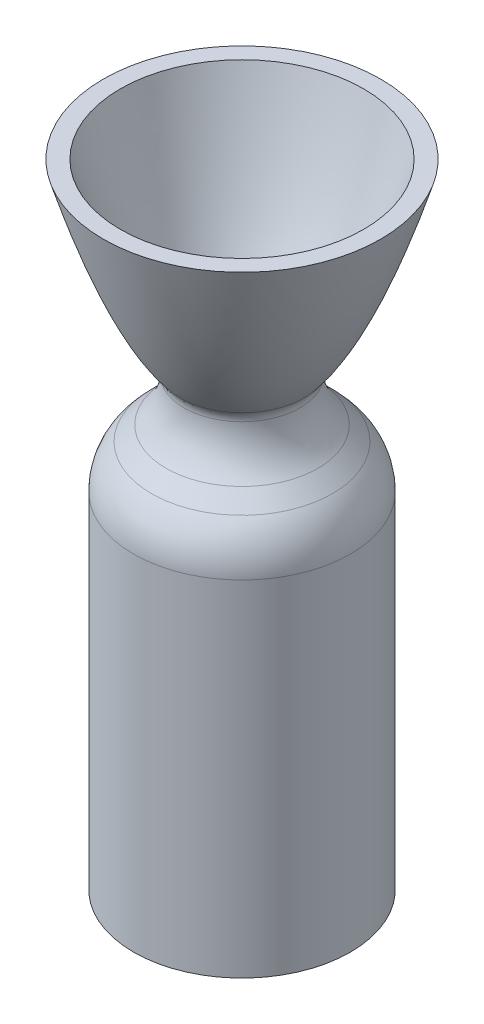
SolidWorks part; units mm, degrees
material "AISI 1020"
ref_plane "Front Plane" through (0, 0, 0) normal (0, 0, 1) x (1, 0, 0)
ref_plane "Top Plane" through (0, 0, 0) normal (0, 1, 0) x (1, 0, 0)
ref_plane "Right Plane" through (0, 0, 0) normal (1, 0, 0) x (0, 0, -1)
sketch "Sketch1" plane through (0, 0, 0) normal (0, 0, 1) x (1, 0, 0)
  line L0 (-0.0055, 165.816) -> (-0.0055, -134.6871) construction
  line L1 (71.7275, 109.9275) -> (81.7275, 109.9275)
  line L4 (53.8815, -59.7275) -> (53.8815, -262.9275)
  line L7 (63.8815, -59.761) -> (63.8815, -262.9447)
  line L8 (53.8815, -262.9275) -> (63.8815, -262.9447)
  spline S0 degree 2 poles (26.7953, 6.5094) (49.2614, 34.6361) (71.7275, 109.9275) knots 0 0 0 1 1 1 construction
  spline S1 degree 2 poles (26.7953, 6.5094) (49.2614, 34.6361) (71.7275, 109.9275) knots 0 0 0 1 1 1
  spline S2 degree 4 poles (24.1269, -0.7179) (24.126, -0.7018) (24.1243, -0.6738) (24.121, -0.6546) (24.115, -0.5166) (24.1058, -0.4369) (24.0994, -0.1066) (24.0979, 0.0018) (24.102, 0.2678) (24.1085, 0.4272) (24.1205, 0.6469) (24.1414, 0.9016) (24.1752, 1.2027) (24.2265, 1.5422) (24.2905, 1.8812) (24.3671, 2.2165) (24.4563, 2.5494) (24.5577, 2.8783) (24.6716, 3.2035) (24.7972, 3.5238) (24.9353, 3.8398) (25.0841, 4.1494) (25.246, 4.4549) (25.4165, 4.7515) (25.6025, 5.0459) (25.7918, 5.3257) (26.0044, 5.6109) (26.1789, 5.8331) (26.3663, 6.0501) (26.5046, 6.2088) (26.757, 6.4728) (26.837, 6.5526) (27.1016, 6.806) (27.1881, 6.8783) (27.2854, 6.9667) (27.3038, 6.9803) (27.3264, 7.0004) knots 0 0 0 0 0 0.005192 0.010384 0.020768 0.041536 0.082569 0.102427 0.122284 0.142142 0.162 0.201716 0.241431 0.281147 0.320863 0.360578 0.400294 0.44001 0.479725 0.519441 0.559156 0.598872 0.638588 0.678303 0.718019 0.757735 0.79745 0.837166 0.857024 0.876882 0.916597 0.958047 0.979024 0.989512 1 1 1 1 1 construction
  spline S3 degree 4 poles (24.0991, 0.0002) (24.0991, 0.0361) (24.0996, 0.1103) (24.102, 0.2678) (24.1085, 0.4272) (24.1205, 0.6469) (24.1414, 0.9016) (24.1752, 1.2027) (24.2265, 1.5422) (24.2905, 1.8812) (24.3671, 2.2165) (24.4563, 2.5494) (24.5577, 2.8783) (24.6716, 3.2035) (24.7972, 3.5238) (24.9353, 3.8398) (25.0841, 4.1494) (25.246, 4.4549) (25.4165, 4.7515) (25.6025, 5.0459) (25.7918, 5.3257) (26.0044, 5.6109) (26.1789, 5.8331) (26.3663, 6.0501) (26.5046, 6.2088) (26.6704, 6.3823) (26.7445, 6.4586) (26.7953, 6.5094) knots 0.082569 0.082569 0.082569 0.082569 0.082569 0.102427 0.122284 0.142142 0.162 0.201716 0.241431 0.281147 0.320863 0.360578 0.400294 0.44001 0.479725 0.519441 0.559156 0.598872 0.638588 0.678303 0.718019 0.757735 0.79745 0.837166 0.857024 0.876882 0.916597 0.916597 0.916597 0.916597 0.916597
  spline S4 degree 4 poles (24.2082, 2.808) (24.2014, 2.7166) (24.1882, 2.5518) (24.1642, 2.1754) (24.1352, 1.6881) (24.1148, 1.1018) (24.103, 0.6556) (24.0988, 0.1104) (24.0988, -0.0999) (24.102, -0.543) (24.1083, -0.824) (24.1178, -1.1947) (24.1304, -1.5133) (24.1462, -1.8618) (24.1652, -2.1935) (24.1928, -2.6179) (24.2323, -3.1219) (24.3033, -3.8798) (24.4231, -4.8863) (24.5995, -6.0566) (24.8509, -7.385) (25.1518, -8.7034) (25.5018, -10.0095) (25.9004, -11.3017) (26.3469, -12.5779) (26.841, -13.8367) (27.3817, -15.076) (27.9685, -16.2944) (28.6001, -17.4898) (29.2765, -18.6611) (29.9954, -19.8056) (30.758, -20.9237) (31.4592, -21.8743) (32.0887, -22.6733) (32.6241, -23.3203) (33.0723, -23.8398) (33.5085, -24.3297) (33.9358, -24.7883) (34.2456, -25.1137) (34.6121, -25.4859) (34.7661, -25.6398) (35.1509, -26.0187) (35.4776, -26.3286) (35.905, -26.7273) (36.2395, -27.0242) (36.5192, -27.2707) (36.6465, -27.3798) (36.7148, -27.4387) (36.7496, -27.4686) knots 0 0 0 0 0 0.010393 0.020785 0.041571 0.062104 0.072371 0.082638 0.092575 0.102512 0.112449 0.122387 0.132324 0.142261 0.152198 0.162135 0.18201 0.201884 0.241633 0.281382 0.32113 0.360879 0.400628 0.440377 0.480126 0.519874 0.559623 0.599372 0.639121 0.67887 0.718618 0.758367 0.798116 0.81799 0.837865 0.857739 0.877613 0.897488 0.907425 0.917362 0.927629 0.937896 0.958429 0.979215 0.989607 0.994804 1 1 1 1 1 construction
  spline S5 degree 4 poles (24.0991, 0.0002) (24.0991, -0.0704) (24.0996, -0.2134) (24.102, -0.543) (24.1083, -0.824) (24.1178, -1.1947) (24.1304, -1.5133) (24.1462, -1.8618) (24.1652, -2.1935) (24.1928, -2.6179) (24.2323, -3.1219) (24.3033, -3.8798) (24.4231, -4.8863) (24.5995, -6.0566) (24.8509, -7.385) (25.1518, -8.7034) (25.5018, -10.0095) (25.9004, -11.3017) (26.3469, -12.5779) (26.841, -13.8367) (27.3817, -15.076) (27.9685, -16.2944) (28.6001, -17.4898) (29.2765, -18.6611) (29.9954, -19.8056) (30.758, -20.9237) (31.4592, -21.8743) (32.0887, -22.6733) (32.6241, -23.3203) (33.0723, -23.8398) (33.5085, -24.3297) (33.9358, -24.7883) (34.2456, -25.1137) (34.5369, -25.4095) (34.6364, -25.5098) (34.6863, -25.5597) knots 0.082638 0.082638 0.082638 0.082638 0.082638 0.092575 0.102512 0.112449 0.122387 0.132324 0.142261 0.152198 0.162135 0.18201 0.201884 0.241633 0.281382 0.32113 0.360879 0.400628 0.440377 0.480126 0.519874 0.559623 0.599372 0.639121 0.67887 0.718618 0.758367 0.798116 0.81799 0.837865 0.857739 0.877613 0.897488 0.907425 0.917362 0.917362 0.917362 0.917362 0.917362
  spline S6 degree 1 poles (34.6863, -25.5597) (43.2939, -34.1673) knots 0 0 1 1 construction
  spline S7 degree 1 poles (34.6863, -25.5597) (43.2939, -34.1673) knots 0 0 1 1
  spline S8 degree 4 poles (53.7724, -62.5352) (53.7792, -62.4464) (53.7924, -62.2737) (53.8104, -62.0016) (53.8309, -61.6599) (53.848, -61.2921) (53.8616, -60.9658) (53.8717, -60.5752) (53.8784, -60.2939) (53.8818, -59.8332) (53.8818, -59.6304) (53.8786, -59.1816) (53.8723, -58.9048) (53.8628, -58.5326) (53.8502, -58.2128) (53.8304, -57.7816) (53.8004, -57.281) (53.7562, -56.688) (53.6773, -55.8485) (53.5774, -55.0082) (53.4567, -54.1724) (53.2868, -53.1724) (53.0921, -52.1774) (52.8664, -51.1885) (52.61, -50.2075) (52.3293, -49.2331) (52.0243, -48.266) (51.6335, -47.1491) (51.1395, -45.8904) (50.5987, -44.651) (50.0121, -43.4327) (49.3801, -42.2371) (48.7041, -41.0662) (47.9845, -39.921) (47.2231, -38.8041) (46.5199, -37.8515) (45.8935, -37.0557) (45.3528, -36.4034) (44.9151, -35.8942) (44.5148, -35.447) (44.1815, -35.0846) (43.8739, -34.7603) (43.6741, -34.5515) (43.3653, -34.2383) (43.2159, -34.0889) (42.8277, -33.7066) (42.5041, -33.3998) (42.0741, -32.9986) (41.7412, -32.7033) (41.4607, -32.4559) (41.3338, -32.3472) (41.2653, -32.2883) (41.2305, -32.2583) knots 0 0 0 0 0 0.010393 0.020785 0.031178 0.041571 0.051838 0.062104 0.072371 0.082638 0.092575 0.102512 0.112449 0.122387 0.132324 0.142261 0.162135 0.18201 0.201884 0.241633 0.261507 0.281382 0.32113 0.360879 0.380754 0.400628 0.440377 0.480126 0.519874 0.559623 0.599372 0.639121 0.67887 0.718618 0.758367 0.798116 0.81799 0.837865 0.857739 0.877613 0.887551 0.897488 0.907425 0.917362 0.927629 0.937896 0.958429 0.979215 0.989607 0.994804 1 1 1 1 1 construction
  spline S9 degree 4 poles (53.8815, -59.7275) (53.8815, -59.657) (53.881, -59.5154) (53.8786, -59.1816) (53.8723, -58.9048) (53.8628, -58.5326) (53.8502, -58.2128) (53.8304, -57.7816) (53.8004, -57.281) (53.7562, -56.688) (53.6773, -55.8485) (53.5774, -55.0082) (53.4567, -54.1724) (53.2868, -53.1724) (53.0921, -52.1774) (52.8664, -51.1885) (52.61, -50.2075) (52.3293, -49.2331) (52.0243, -48.266) (51.6335, -47.1491) (51.1395, -45.8904) (50.5987, -44.651) (50.0121, -43.4327) (49.3801, -42.2371) (48.7041, -41.0662) (47.9845, -39.921) (47.2231, -38.8041) (46.5199, -37.8515) (45.8935, -37.0557) (45.3528, -36.4034) (44.9151, -35.8942) (44.5148, -35.447) (44.1815, -35.0846) (43.8739, -34.7603) (43.6741, -34.5515) (43.4444, -34.3185) (43.3438, -34.2172) (43.2939, -34.1673) knots 0.082638 0.082638 0.082638 0.082638 0.082638 0.092575 0.102512 0.112449 0.122387 0.132324 0.142261 0.162135 0.18201 0.201884 0.241633 0.261507 0.281382 0.32113 0.360879 0.380754 0.400628 0.440377 0.480126 0.519874 0.559623 0.599372 0.639121 0.67887 0.718618 0.758367 0.798116 0.81799 0.837865 0.857739 0.877613 0.887551 0.897488 0.907425 0.917362 0.917362 0.917362 0.917362 0.917362
  spline S10 degree 2 poles (36.8348, 6.4922) (59.2902, 34.6275) (81.7275, 109.9275) knots 0 0 0 1 1 1 construction
  spline S11 degree 2 poles (36.8348, 6.4922) (59.2902, 34.6275) (81.7275, 109.9275) knots 0 0 0 1 1 1
  spline S12 degree 4 poles (34.1664, -0.7351) (34.1655, -0.719) (34.1638, -0.691) (34.1605, -0.6718) (34.1546, -0.5338) (34.1454, -0.4541) (34.1389, -0.1238) (34.1375, -0.0154) (34.1416, 0.2506) (34.148, 0.4101) (34.1601, 0.6298) (34.181, 0.8844) (34.2147, 1.1855) (34.266, 1.525) (34.3301, 1.864) (34.4067, 2.1993) (34.4959, 2.5322) (34.5973, 2.8611) (34.7112, 3.1863) (34.8367, 3.5066) (34.9748, 3.8227) (35.1236, 4.1323) (35.2856, 4.4378) (35.456, 4.7343) (35.6421, 5.0287) (35.8313, 5.3085) (36.0439, 5.5937) (36.2184, 5.8159) (36.4059, 6.0329) (36.5441, 6.1916) (36.7965, 6.4556) (36.8765, 6.5354) (37.1411, 6.7888) (37.2276, 6.8611) (37.3249, 6.9496) (37.3433, 6.9632) (37.3659, 6.9832) knots 0 0 0 0 0 0.005192 0.010384 0.020768 0.041536 0.082569 0.102427 0.122284 0.142142 0.162 0.201716 0.241431 0.281147 0.320863 0.360578 0.400294 0.44001 0.479725 0.519441 0.559156 0.598872 0.638588 0.678303 0.718019 0.757735 0.79745 0.837166 0.857024 0.876882 0.916597 0.958047 0.979024 0.989512 1 1 1 1 1 construction
  spline S13 degree 4 poles (34.1386, -0.017) (34.1386, 0.0189) (34.1391, 0.0931) (34.1416, 0.2506) (34.148, 0.4101) (34.1601, 0.6298) (34.181, 0.8844) (34.2147, 1.1855) (34.266, 1.525) (34.3301, 1.864) (34.4067, 2.1993) (34.4959, 2.5322) (34.5973, 2.8611) (34.7112, 3.1863) (34.8367, 3.5066) (34.9748, 3.8227) (35.1236, 4.1323) (35.2856, 4.4378) (35.456, 4.7343) (35.6421, 5.0287) (35.8313, 5.3085) (36.0439, 5.5937) (36.2184, 5.8159) (36.4059, 6.0329) (36.5441, 6.1916) (36.71, 6.3651) (36.7841, 6.4415) (36.8348, 6.4922) knots 0.082569 0.082569 0.082569 0.082569 0.082569 0.102427 0.122284 0.142142 0.162 0.201716 0.241431 0.281147 0.320863 0.360578 0.400294 0.44001 0.479725 0.519441 0.559156 0.598872 0.638588 0.678303 0.718019 0.757735 0.79745 0.837166 0.857024 0.876882 0.916597 0.916597 0.916597 0.916597 0.916597
  spline S14 degree 4 poles (34.2478, 2.7908) (34.2409, 2.6994) (34.2278, 2.5346) (34.2038, 2.1582) (34.1748, 1.6709) (34.1544, 1.0846) (34.1425, 0.6384) (34.1384, 0.0932) (34.1383, -0.1171) (34.1415, -0.5602) (34.1478, -0.8412) (34.1573, -1.2118) (34.17, -1.5304) (34.1858, -1.8789) (34.2047, -2.2107) (34.2324, -2.6351) (34.2718, -3.139) (34.3428, -3.897) (34.4627, -4.9035) (34.639, -6.0737) (34.8904, -7.4022) (35.1913, -8.7206) (35.5413, -10.0266) (35.9399, -11.3188) (36.3865, -12.5951) (36.8805, -13.8539) (37.4212, -15.0932) (38.008, -16.3116) (38.6397, -17.5069) (39.3161, -18.6783) (40.035, -19.8228) (40.7976, -20.9409) (41.4987, -21.8914) (42.1283, -22.6905) (42.6637, -23.3374) (43.1118, -23.857) (43.548, -24.3468) (43.9754, -24.8055) (44.2851, -25.1309) (44.6516, -25.5031) (44.8056, -25.657) (45.1904, -26.0359) (45.5171, -26.3458) (45.9446, -26.7444) (46.2791, -27.0414) (46.5587, -27.2879) (46.686, -27.397) (46.7544, -27.4558) (46.7891, -27.4857) knots 0 0 0 0 0 0.010393 0.020785 0.041571 0.062104 0.072371 0.082638 0.092575 0.102512 0.112449 0.122387 0.132324 0.142261 0.152198 0.162135 0.18201 0.201884 0.241633 0.281382 0.32113 0.360879 0.400628 0.440377 0.480126 0.519874 0.559623 0.599372 0.639121 0.67887 0.718618 0.758367 0.798116 0.81799 0.837865 0.857739 0.877613 0.897488 0.907425 0.917362 0.927629 0.937896 0.958429 0.979215 0.989607 0.994804 1 1 1 1 1 construction
  spline S15 degree 4 poles (34.1386, -0.017) (34.1386, -0.0875) (34.1391, -0.2306) (34.1415, -0.5602) (34.1478, -0.8412) (34.1573, -1.2118) (34.17, -1.5304) (34.1858, -1.8789) (34.2047, -2.2107) (34.2324, -2.6351) (34.2718, -3.139) (34.3428, -3.897) (34.4627, -4.9035) (34.639, -6.0737) (34.8904, -7.4022) (35.1913, -8.7206) (35.5413, -10.0266) (35.9399, -11.3188) (36.3865, -12.5951) (36.8805, -13.8539) (37.4212, -15.0932) (38.008, -16.3116) (38.6397, -17.5069) (39.3161, -18.6783) (40.035, -19.8228) (40.7976, -20.9409) (41.4987, -21.8914) (42.1283, -22.6905) (42.6637, -23.3374) (43.1118, -23.857) (43.548, -24.3468) (43.9754, -24.8055) (44.2851, -25.1309) (44.5764, -25.4267) (44.676, -25.527) (44.7258, -25.5768) knots 0.082638 0.082638 0.082638 0.082638 0.082638 0.092575 0.102512 0.112449 0.122387 0.132324 0.142261 0.152198 0.162135 0.18201 0.201884 0.241633 0.281382 0.32113 0.360879 0.400628 0.440377 0.480126 0.519874 0.559623 0.599372 0.639121 0.67887 0.718618 0.758367 0.798116 0.81799 0.837865 0.857739 0.877613 0.897488 0.907425 0.917362 0.917362 0.917362 0.917362 0.917362
  spline S16 degree 1 poles (44.7258, -25.5768) (53.3335, -34.1845) knots 0 0 1 1 construction
  spline S17 degree 1 poles (44.7258, -25.5768) (53.3335, -34.1845) knots 0 0 1 1
  spline S18 degree 4 poles (63.768, -62.5686) (63.775, -62.4798) (63.7884, -62.3071) (63.8069, -62.035) (63.8279, -61.6934) (63.8456, -61.3255) (63.8596, -60.9993) (63.8704, -60.6087) (63.8776, -60.3275) (63.8816, -59.8667) (63.882, -59.6639) (63.8795, -59.2151) (63.8736, -58.9383) (63.8647, -58.5661) (63.8525, -58.2463) (63.8334, -57.815) (63.8042, -57.3144) (63.7609, -56.7213) (63.6833, -55.8817) (63.5847, -55.0412) (63.4653, -54.2053) (63.2969, -53.205) (63.1037, -52.2097) (62.8796, -51.2205) (62.6247, -50.239) (62.3455, -49.2642) (62.0421, -48.2966) (61.653, -47.1792) (61.1609, -45.9197) (60.6221, -44.6794) (60.0373, -43.4603) (59.4072, -42.2637) (58.733, -41.0917) (58.0151, -39.9454) (57.2555, -38.8273) (56.5537, -37.8736) (55.9286, -37.0769) (55.3889, -36.4237) (54.952, -35.9139) (54.5523, -35.466) (54.2196, -35.1032) (53.9125, -34.7784) (53.713, -34.5693) (53.4047, -34.2555) (53.2556, -34.106) (52.8679, -33.7231) (52.5448, -33.4157) (52.1154, -33.0139) (51.783, -32.7181) (51.5028, -32.4703) (51.3761, -32.3614) (51.3078, -32.3023) (51.273, -32.2723) knots 0 0 0 0 0 0.010393 0.020785 0.031178 0.041571 0.051838 0.062104 0.072371 0.082638 0.092575 0.102512 0.112449 0.122387 0.132324 0.142261 0.162135 0.18201 0.201884 0.241633 0.261507 0.281382 0.32113 0.360879 0.380754 0.400628 0.440377 0.480126 0.519874 0.559623 0.599372 0.639121 0.67887 0.718618 0.758367 0.798116 0.81799 0.837865 0.857739 0.877613 0.887551 0.897488 0.907425 0.917362 0.927629 0.937896 0.958429 0.979215 0.989607 0.994804 1 1 1 1 1 construction
  spline S19 degree 4 poles (63.8815, -59.761) (63.8816, -59.6905) (63.8813, -59.5489) (63.8795, -59.2151) (63.8736, -58.9383) (63.8647, -58.5661) (63.8525, -58.2463) (63.8334, -57.815) (63.8042, -57.3144) (63.7609, -56.7213) (63.6833, -55.8817) (63.5847, -55.0412) (63.4653, -54.2053) (63.2969, -53.205) (63.1037, -52.2097) (62.8796, -51.2205) (62.6247, -50.239) (62.3455, -49.2642) (62.0421, -48.2966) (61.653, -47.1792) (61.1609, -45.9197) (60.6221, -44.6794) (60.0373, -43.4603) (59.4072, -42.2637) (58.733, -41.0917) (58.0151, -39.9454) (57.2555, -38.8273) (56.5537, -37.8736) (55.9286, -37.0769) (55.3889, -36.4237) (54.952, -35.9139) (54.5523, -35.466) (54.2196, -35.1032) (53.9125, -34.7784) (53.713, -34.5693) (53.4837, -34.3359) (53.3832, -34.2344) (53.3335, -34.1845) knots 0.082638 0.082638 0.082638 0.082638 0.082638 0.092575 0.102512 0.112449 0.122387 0.132324 0.142261 0.162135 0.18201 0.201884 0.241633 0.261507 0.281382 0.32113 0.360879 0.380754 0.400628 0.440377 0.480126 0.519874 0.559623 0.599372 0.639121 0.67887 0.718618 0.758367 0.798116 0.81799 0.837865 0.857739 0.877613 0.887551 0.897488 0.907425 0.917362 0.917362 0.917362 0.917362 0.917362
  dimension "D1" = 24.1046
  dimension "D2" = 53.8871
  dimension "D3" = 203.2
  dimension "D4" = 10
  dimension "D5" = 10
  dimension "D7" = 24.0991
  dimension "D8" = 26.7953
  dimension "D9" = 34.6863
  dimension "D10" = 0.0002
revolve "Revolve2" add sketch "Sketch1" angle 360 about L0
